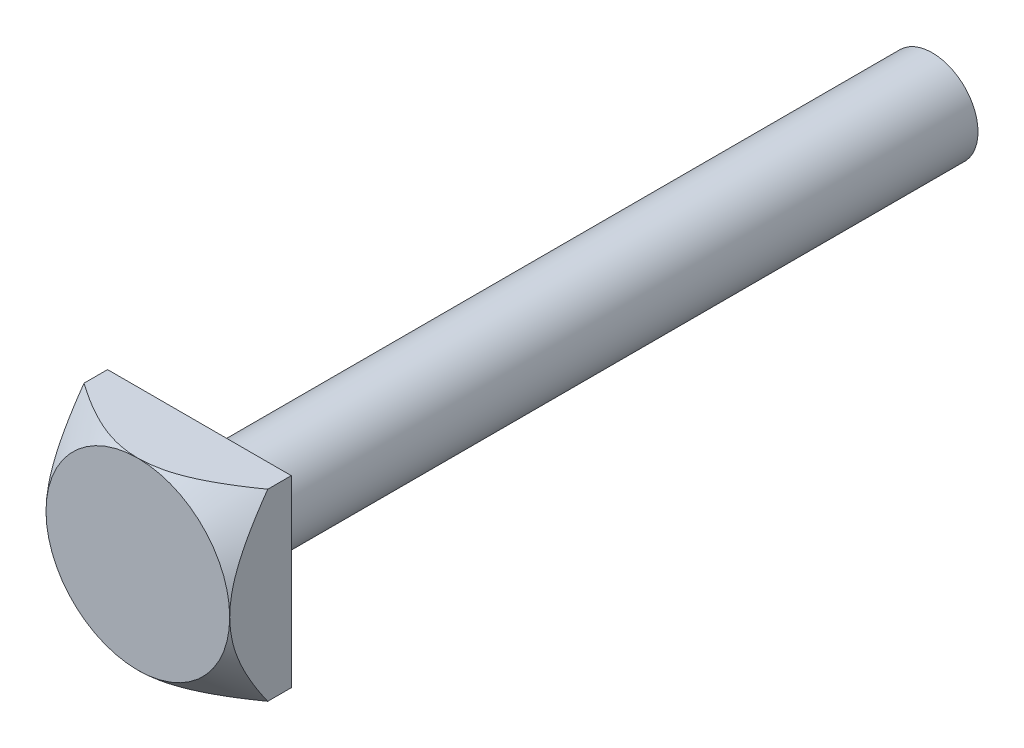
SolidWorks part; units mm, degrees
ref_plane "Front Plane" through (0, 0, 0) normal (0, 0, 1) x (1, 0, 0)
ref_plane "Top Plane" through (0, 0, 0) normal (0, 1, 0) x (1, 0, 0)
ref_plane "Right Plane" through (0, 0, 0) normal (1, 0, 0) x (0, 0, -1)
sketch "Sketch1" plane through (0, 0, 0) normal (0, 0, 1) x (1, 0, 0)
  line L1 (-9.55, 9.55) -> (9.55, 9.55)
  line L2 (-9.55, 9.55) -> (-9.55, -9.55)
  line L3 (-9.55, -9.55) -> (9.55, -9.55)
  line L4 (9.55, 9.55) -> (9.55, -9.55)
  line L5 (-9.55, 9.55) -> (9.55, -9.55) construction
  line L6 (-9.55, -9.55) -> (9.55, 9.55) construction
  point P0 (0, 0)
  dimension "D1" = 19.1
  dimension "D2" = 19.1
extrude "Boss-Extrude1" add sketch "Sketch1" against normal blind 6.4
sketch "Sketch2" plane through (0, 0, -6.4) normal (0, 0, -1) x (-1, 0, 0)
  circle A0 centre (0, 0) radius 4.75
  dimension "D1" = 9.5
extrude "Boss-Extrude2" add sketch "Sketch2" along normal blind 76.2
sketch "Sketch3" plane through (0, 0, 0) normal (0, 0, 1) x (1, 0, 0)
  line L0 (9.55, 9.55) -> (-9.55, 9.55) construction
  circle A0 centre (0, 0) radius 9.55
extrude "Cut-Extrude2" cut sketch "Sketch3" against normal blind 6.4 draft 45 flip side to cut contours A0
